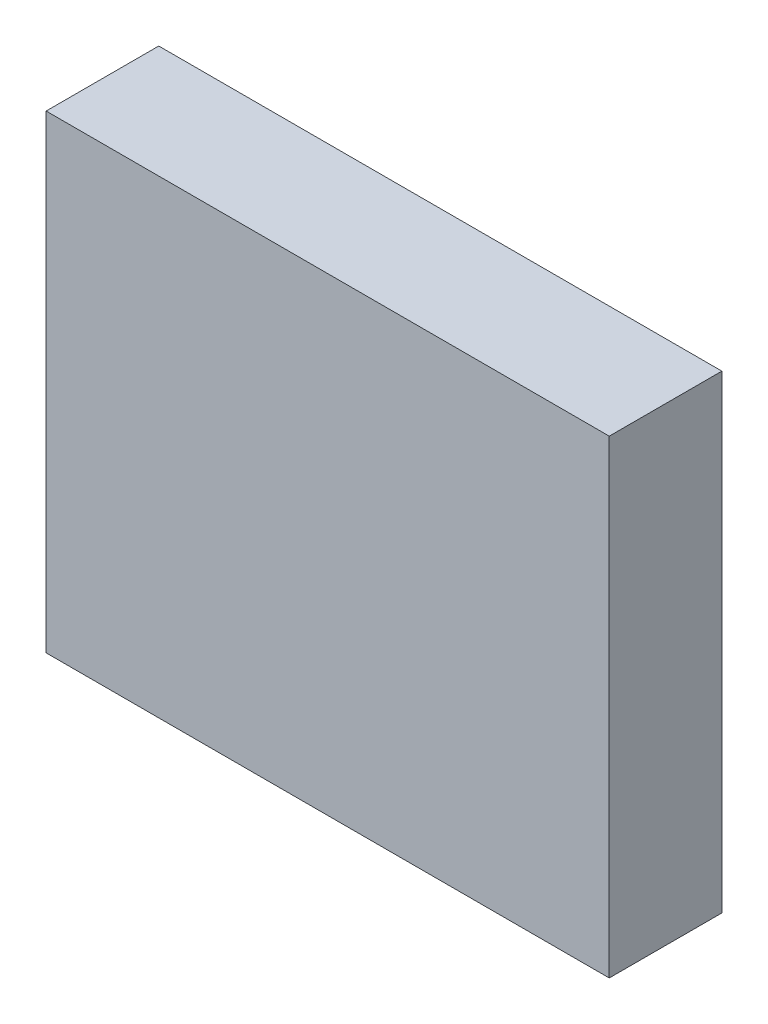
SolidWorks part; units mm, degrees
ref_plane "Front Plane" through (0, 0, 0) normal (0, 0, 1) x (1, 0, 0)
ref_plane "Top Plane" through (0, 0, 0) normal (0, 1, 0) x (1, 0, 0)
ref_plane "Right Plane" through (0, 0, 0) normal (1, 0, 0) x (0, 0, -1)
other "Configuration Table"
sketch "Sketch1" plane through (0, 0, 0) normal (0, 0, 1) x (1, 0, 0)
  line L1 (300, 1680) -> (600, 1680)
  line L2 (300, 1680) -> (300, 1930)
  line L3 (300, 1930) -> (600, 1930)
  line L4 (600, 1680) -> (600, 1930)
extrude "STORE_sog1_kondenser_1" add sketch "Sketch1" against normal blind 60 from offset 240 separate body
